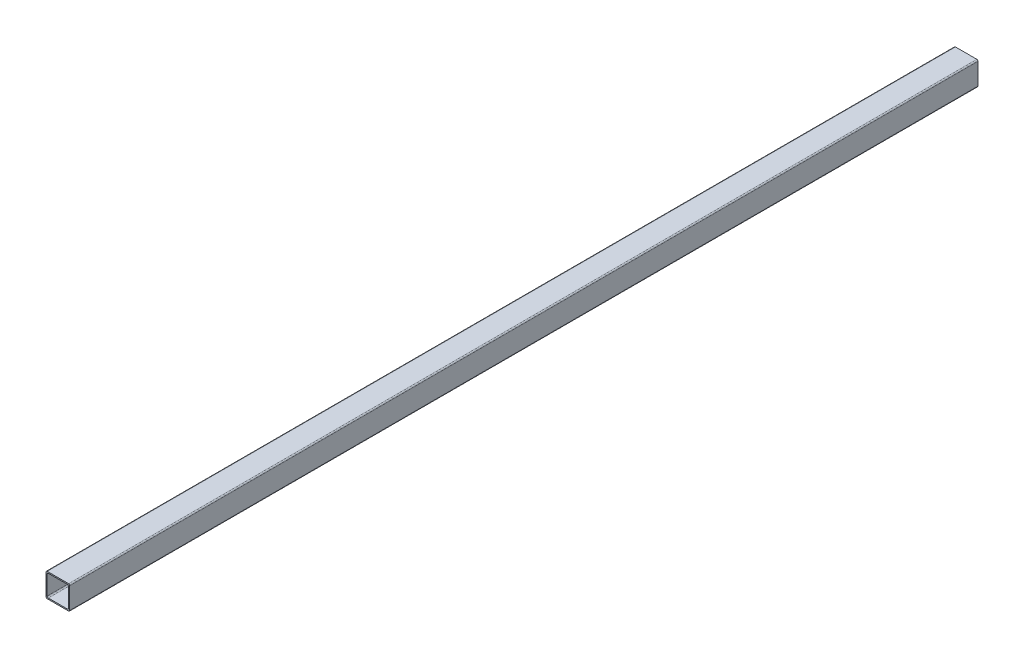
SolidWorks part; units mm, degrees
ref_plane "Спереди" through (0, 0, 0) normal (0, 0, 1) x (1, 0, 0)
ref_plane "Сверху" through (0, 0, 0) normal (0, 1, 0) x (1, 0, 0)
ref_plane "Справа" through (0, 0, 0) normal (1, 0, 0) x (0, 0, -1)
sketch "Эскиз1" plane through (0, 0, 0) normal (0, 0, 1) x (1, 0, 0)
  line L1 (-18, 20) -> (18, 20)
  line L2 (-20, 18) -> (-20, -18)
  line L3 (-18, -20) -> (18, -20)
  line L4 (20, 18) -> (20, -18)
  line L5 (-20, 20) -> (20, -20) construction
  line L6 (-20, -20) -> (20, 20) construction
  line L7 (16, -18) -> (-16, -18)
  line L8 (18, -16) -> (18, 16)
  line L9 (16, 18) -> (-16, 18)
  line L10 (-18, -16) -> (-18, 16)
  line L11 (18, -18) -> (-18, 18) construction
  line L12 (18, 18) -> (-18, -18) construction
  arc A0 (18, 20) -> (20, 18) centre (18, 18) cw
  arc A1 (18, 16) -> (16, 18) centre (16, 16) ccw
  arc A2 (16, -18) -> (18, -16) centre (16, -16) ccw
  arc A3 (18, -20) -> (20, -18) centre (18, -18) ccw
  arc A4 (-16, -18) -> (-18, -16) centre (-16, -16) cw
  arc A5 (-20, -18) -> (-18, -20) centre (-18, -18) ccw
  arc A6 (-18, 20) -> (-20, 18) centre (-18, 18) ccw
  arc A7 (-16, 18) -> (-18, 16) centre (-16, 16) ccw
  point P0 (0, 0)
  point P6 (0, 0)
  dimension "D5" = 2
  dimension "D1" = 40
  dimension "D2" = 40
  dimension "D3" = 2
  dimension "D4" = 2
extrude "Бобышка-Вытянуть1" add sketch "Эскиз1" along normal blind 1530
